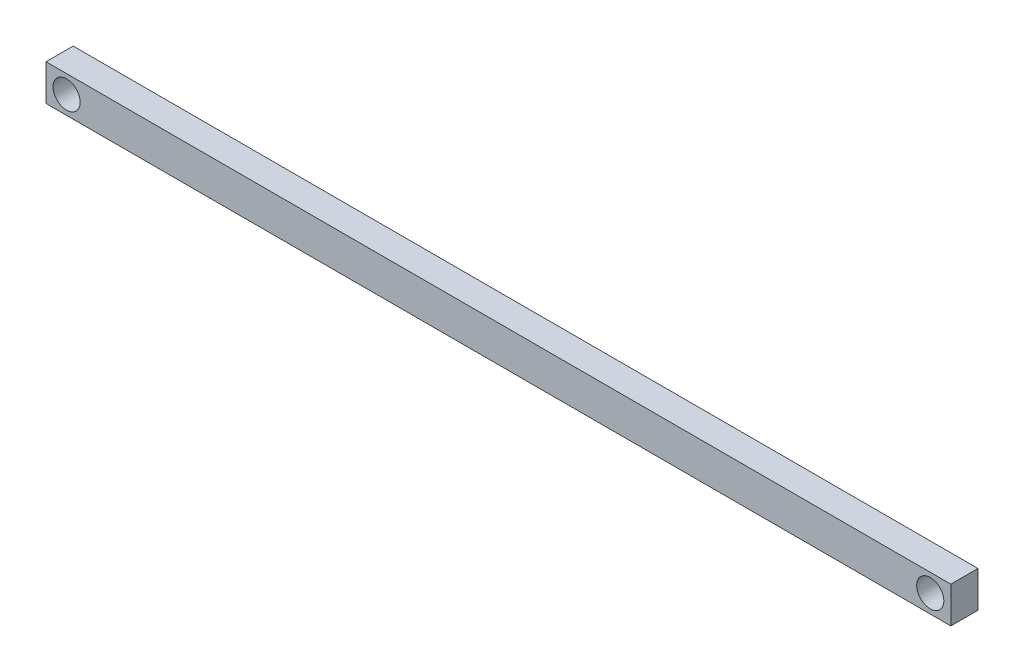
SolidWorks part; units mm, degrees
ref_plane "Front Plane" through (0, 0, 0) normal (0, 0, 1) x (1, 0, 0)
ref_plane "Top Plane" through (0, 0, 0) normal (0, 1, 0) x (1, 0, 0)
ref_plane "Right Plane" through (0, 0, 0) normal (1, 0, 0) x (0, 0, -1)
sketch "Sketch1" plane through (0, 0, 0) normal (0, 0, 1) x (1, 0, 0)
  line L1 (-250, 10) -> (250, 10)
  line L2 (-250, 10) -> (-250, -10)
  line L3 (-250, -10) -> (250, -10)
  line L4 (250, 10) -> (250, -10)
  line L5 (-250, 10) -> (250, -10) construction
  line L6 (-250, -10) -> (250, 10) construction
  circle A0 centre (-238.62, 0) radius 7.5
  circle A1 centre (238.62, 0) radius 7.5
  point P0 (0, 0)
  dimension "D4" = 15
  dimension "D5" = 15
  dimension "D1" = 500
  dimension "D2" = 477.24
  dimension "D3" = 238.62
  dimension "D6" = 20
extrude "Boss-Extrude1" add sketch "Sketch1" along normal blind 15
